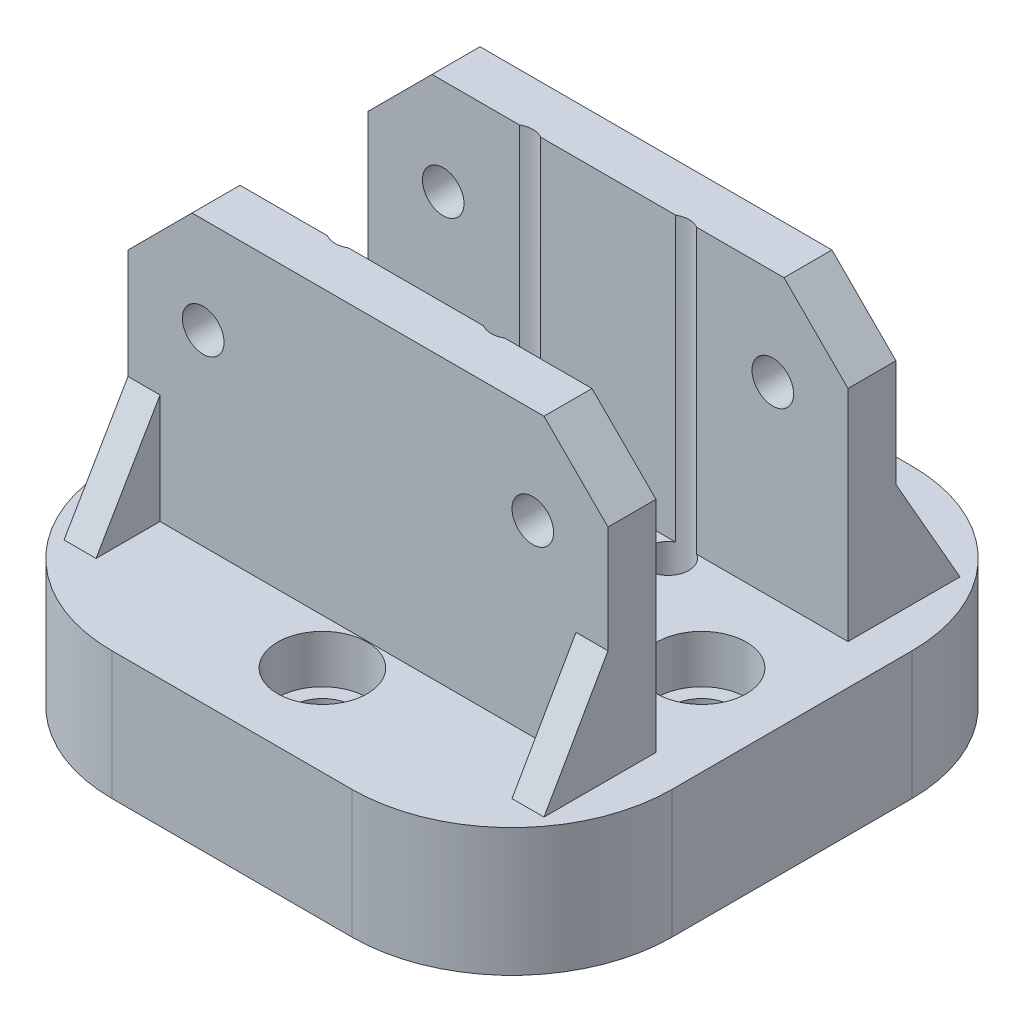
SolidWorks part; units mm, degrees
material "ABS"
ref_plane "前视基准面" through (0, 0, 0) normal (0, 0, 1) x (1, 0, 0)
ref_plane "上视基准面" through (0, 0, 0) normal (0, 1, 0) x (1, 0, 0)
ref_plane "右视基准面" through (0, 0, 0) normal (1, 0, 0) x (0, 0, -1)
other "Configuration Table"
sketch "草图2" plane through (0, 0, 0) normal (0, 0, 1) x (1, 0, 0)
  line L0 (0, 17.5458) -> (0, -16.2036) construction
  line L1 (-11, 11) -> (11, 11)
  line L2 (-15, 7) -> (-15, -11)
  line L3 (-15, -11) -> (15, -11)
  line L5 (-17.0124, 0) -> (19.7175, 0) construction
  line L7 (-15, 7) -> (-11, 11)
  line L8 (15, 7) -> (11, 11)
  line L9 (15, 7) -> (15, -11)
  circle A0 centre (-10.3, 5) radius 1.3
  circle A1 centre (10.3, 5) radius 1.3
  point P0 (0, 0)
  point P4 (0, -11)
  point P15 (0, 11)
  dimension "D4" = 2.6
  dimension "D1" = 18
  dimension "D2" = 15
  dimension "D3" = 16
  dimension "D5" = 11
  dimension "D6" = 22
  dimension "D7" = 10.3
extrude "凸台-拉伸1" add sketch "草图2" along normal mid plane 18
sketch "草图3" plane through (0, 0, 0) normal (0, 0, 1) x (1, 0, 0)
  line L0 (-15, 7) -> (-15, -11) construction
  line L1 (-15, -6.7) -> (15, -6.7)
  line L2 (-15, -6.7) -> (-15, 14.1356)
  line L3 (-15, 14.1356) -> (15, 14.1356)
  line L4 (15, -6.7) -> (15, 14.1356)
  line L5 (15, -11) -> (15, 7) construction
  line L6 (-15, -11) -> (15, -11) construction
  dimension "D1" = 4.3
extrude "切除-拉伸1" cut sketch "草图3" against normal mid plane 12
sketch "草图5" plane through (0, 0, 0) normal (0, 1, 0) x (1, 0, 0)
  line L0 (-19.7269, 0) -> (0, 0) construction
  line L1 (0, 0) -> (0, 17.6779) construction
  line L2 (0, 0) -> (-14.1421, 14.1421) construction
  circle A0 centre (0, 0) radius 1.3
  circle A1 centre (-4.879, 4.879) radius 1.3
  circle A2 centre (-11.85, 0) radius 1.9
  circle A3 centre (0, 11.85) radius 1.9
  circle A4 centre (4.879, 4.879) radius 1.3
  circle A5 centre (11.85, 0) radius 1.9
  circle A6 centre (4.879, -4.879) radius 1.3
  circle A7 centre (0, -11.85) radius 1.9
  circle A8 centre (-4.879, -4.879) radius 1.3
  point P25 (0, 0)
  dimension "D2" = 2.6
  dimension "D3" = 2.6
  dimension "D6" = 3.8
  dimension "D1" = 45
  dimension "D4" = 11.85
  dimension "D5" = 6.9
  dimension "D7" = 4
sketch "草图6" plane through (0, 0, 0) normal (0, 1, 0) x (1, 0, 0)
  line L1 (-7.5, -17.5) -> (7.5, -17.5)
  line L2 (-17.5, -7.5) -> (-17.5, 7.5)
  line L3 (-7.5, 17.5) -> (7.5, 17.5)
  line L4 (17.5, -7.5) -> (17.5, 7.5)
  line L5 (-17.5, -17.5) -> (17.5, 17.5) construction
  line L6 (-17.5, 17.5) -> (17.5, -17.5) construction
  arc A0 (-17.5, 7.5) -> (-7.5, 17.5) centre (-7.5, 7.5) cw
  arc A1 (-7.5, -17.5) -> (-17.5, -7.5) centre (-7.5, -7.5) cw
  arc A2 (17.5, 7.5) -> (7.5, 17.5) centre (7.5, 7.5) ccw
  arc A3 (7.5, -17.5) -> (17.5, -7.5) centre (7.5, -7.5) ccw
  point P0 (0, 0)
  dimension "D3" = 10
  dimension "D4" = 10
  dimension "D5" = 10
  dimension "D6" = 10
  dimension "D1" = 35
  dimension "D2" = 35
extrude "凸台-拉伸2" add sketch "草图6" against normal blind 8 from surface at -6.7 starting at face at (0, -6.7, 0)
extrude "切除-拉伸2" cut sketch "草图5" along normal blind 30 from surface at -14.7 starting at face at (0, -14.7, 0)
sketch "草图7" plane through (15, 0, 0) normal (1, 0, 0) x (0, 0, -1)
  line L0 (0, 12.9393) -> (0, -16.8041) construction
  line L1 (-9, 0.3) -> (-13, -6.7)
  line L2 (-9, -6.7) -> (-9, 7) construction
  line L3 (-7.5, -6.7) -> (-17.5, -6.7) construction
  line L4 (-13, -6.7) -> (-9, -6.7)
  line L5 (-9, -6.7) -> (-9, 0.3)
  line L6 (9, -6.7) -> (9, 0.3)
  line L7 (13, -6.7) -> (9, -6.7)
  line L8 (9, 0.3) -> (13, -6.7)
  dimension "D1" = 7
  dimension "D2" = 4
extrude "凸台-拉伸3" add sketch "草图7" against normal blind 2
sketch "草图10" plane through (-15, 0, 0) normal (-1, 0, 0) x (0, 0, 1)
  line L0 (0, 11.4837) -> (0, -16.1999) construction
  line L1 (-9, 0.15) -> (-13, -6.7)
  line L2 (-9, 7) -> (-9, -6.7) construction
  line L3 (-13, -6.7) -> (-9, -6.7)
  line L4 (-9, -6.7) -> (-9, 0.15)
  line L5 (9, -6.7) -> (9, 0.15)
  line L6 (13, -6.7) -> (9, -6.7)
  line L7 (9, 0.15) -> (13, -6.7)
extrude "凸台-拉伸4" add sketch "草图10" against normal blind 2
sketch "草图11" plane through (0, -6.7, 0) normal (0, 1, 0) x (1, 0, 0)
  circle A0 centre (0, 11.85) radius 2.8
  circle A1 centre (11.85, 0) radius 2.8
  circle A2 centre (0, -11.85) radius 2.8
  circle A3 centre (-11.85, 0) radius 2.8
  point P12 (0, 0)
  dimension "D1" = 5.6
  dimension "D2" = 4
extrude "切除-拉伸3" cut sketch "草图11" against normal blind 3
